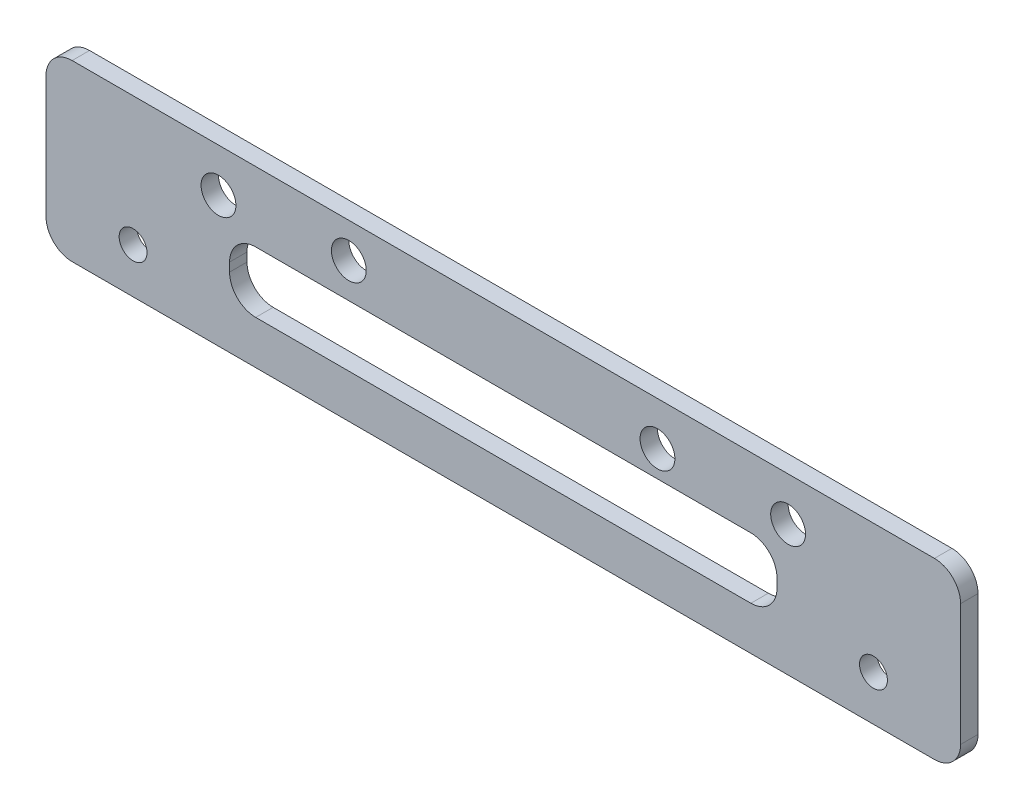
SolidWorks part; units mm, degrees
material "Thornel Mat VMA"
ref_plane "前视基准面" through (0, 0, 0) normal (0, 0, 1) x (1, 0, 0)
ref_plane "上视基准面" through (0, 0, 0) normal (0, 1, 0) x (1, 0, 0)
ref_plane "右视基准面" through (0, 0, 0) normal (1, 0, 0) x (0, 0, -1)
other "Configuration Table"
sketch "草图1" plane through (0, 0, 0) normal (0, 0, 1) x (1, 0, 0)
  line L1 (-52.5, 10) -> (52.5, 10)
  line L2 (-52.5, 10) -> (-52.5, -10)
  line L3 (-52.5, -10) -> (52.5, -10)
  line L4 (52.5, 10) -> (52.5, -10)
  line L5 (-52.5, 10) -> (52.5, -10) construction
  line L6 (-52.5, -10) -> (52.5, 10) construction
  point P0 (0, 0)
  dimension "D1" = 105
  dimension "D2" = 20
extrude "凸台-拉伸1" add sketch "草图1" along normal blind 2
fillet "圆角1" radius 3 4 edges at (52.5, -10, 1) (52.5, 10, 1) (-52.5, -10, 1) (-52.5, 10, 1)
sketch "草图2" plane through (0, 0, 2) normal (0, 0, 1) x (1, 0, 0)
  line L0 (-49.5, -10) -> (49.5, -10) construction
  line L3 (-52.5, 7) -> (-52.5, -7) construction
  line L4 (52.5, -7) -> (52.5, 7) construction
  line L5 (49.5, 10) -> (-49.5, 10) construction
  line L6 (-28.4235, 2) -> (28.4235, 2)
  line L7 (-31.4235, -1) -> (-31.4235, -2)
  line L8 (-28.4235, -5) -> (28.4235, -5)
  line L9 (31.4235, -1) -> (31.4235, -2)
  line L10 (-31.4235, 2) -> (31.4235, -5) construction
  line L11 (-31.4235, -5) -> (31.4235, 2) construction
  circle A0 centre (-32.7, 5) radius 2
  circle A1 centre (-17.7332, 5.9978) radius 2
  circle A2 centre (17.7, 5) radius 2
  circle A3 centre (32.7, 5) radius 2
  circle A5 centre (42.5, -4.8157) radius 1.6
  arc A10 (31.4235, -2) -> (28.4235, -5) centre (28.4235, -2) cw
  arc A11 (31.4235, -1) -> (28.4235, 2) centre (28.4235, -1) ccw
  arc A12 (-28.4235, -5) -> (-31.4235, -2) centre (-28.4235, -2) cw
  arc A13 (-28.4235, 2) -> (-31.4235, -1) centre (-28.4235, -1) ccw
  circle A14 centre (-42.5, -4.8157) radius 1.6
  point P12 (0, -1.5)
  dimension "D1" = 19.8
  dimension "D2" = 15
  dimension "D3" = 19.8
  dimension "D4" = 15
  dimension "D5" = 5
  dimension "D6" = 5
  dimension "D7" = 5
  dimension "D8" = 10
  dimension "D9" = 3.2
  dimension "D12" = 3
  dimension "D13" = 3.2
  dimension "D14" = 10
  dimension "D10" = 5
  dimension "D11" = 7
extrude "切除-拉伸1" cut sketch "草图2" against normal blind 3
